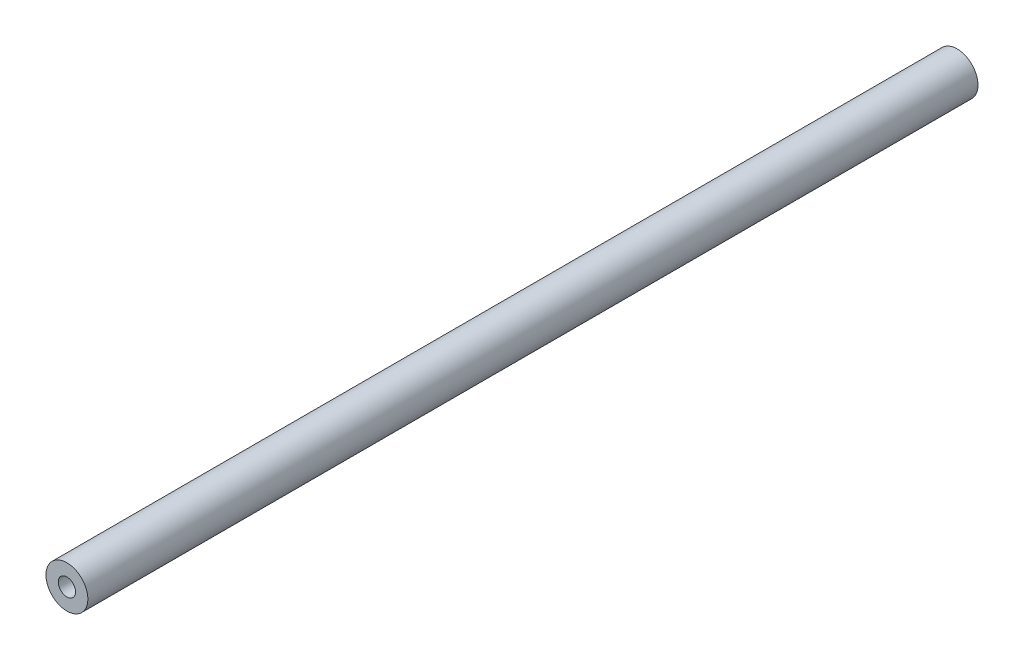
SolidWorks part; units mm, degrees
ref_plane "前视基准面" through (0, 0, 0) normal (0, 0, 1) x (1, 0, 0)
ref_plane "上视基准面" through (0, 0, 0) normal (0, 1, 0) x (1, 0, 0)
ref_plane "右视基准面" through (0, 0, 0) normal (1, 0, 0) x (0, 0, -1)
sketch "草图1" plane through (0, 0, 0) normal (0, 0, 1) x (1, 0, 0)
  circle A0 centre (0, 0) radius 4
  dimension "D1" = 8
extrude "凸台-拉伸1" add sketch "草图1" along normal blind 170
hole_wizard "M4 螺纹孔1" positions "3D草图2" profile "草图5" tap size "M4" standard "Gb"
sketch3d "3D草图2"
  line L0 (0, 0, 170) -> (0, 0, 0) construction
  point P0 (0, 0, 170)
  point P4 (0, 0, 0)
  point P8 (0, 0, 0)
  point P10 (0, 0, 0)
sketch "草图5" plane through (0, 0, 170) normal (1, 0, 0) x (0, -1, 0)
  line L0 (0, 0) -> (0, 16.4914)
  line L1 (0, 16.4914) -> (1.65, 15.5)
  line L2 (1.65, 15.5) -> (1.65, 0)
  line L5 (1.65, 0) -> (0, 0)
  line L10 (0, 16.4914) -> (-1.65, 15.5) construction
  line L11 (0, -6.35) -> (0, 107.95) construction
  dimension "螺纹孔钻头直径" = 3.3
  dimension "螺纹孔钻头深度" = 15.5
  dimension "导头角度" = 118
cosmetic thread "孔螺蚊线1" parameters "D1"=12, "D2"=8
cosmetic thread "孔螺蚊线2" parameters "D1"=12, "D2"=8
cosmetic thread "孔螺蚊线3" parameters "D1"=12, "D2"=8
cosmetic thread "孔螺蚊线4" parameters "D1"=12, "D2"=8
hole_wizard "M4 螺纹孔2" positions "草图7" profile "草图6" tap size "M4" standard "Gb"
sketch "草图7" plane through (0, 0, 0) normal (0, 0, -1) x (-1, 0, 0)
  point P0 (0, 0)
sketch "草图6" plane through (0, 0, 0) normal (1, 0, 0) x (0, 1, 0)
  line L0 (0, 0) -> (0, 16.4914)
  line L1 (0, 16.4914) -> (1.65, 15.5)
  line L2 (1.65, 15.5) -> (1.65, 0)
  line L5 (1.65, 0) -> (0, 0)
  line L10 (0, 16.4914) -> (-1.65, 15.5) construction
  line L11 (0, -6.35) -> (0, 107.95) construction
  dimension "螺纹孔钻头直径" = 3.3
  dimension "螺纹孔钻头深度" = 15.5
  dimension "导头角度" = 118
cosmetic thread "孔螺蚊线5" parameters "D1"=12, "D2"=4
